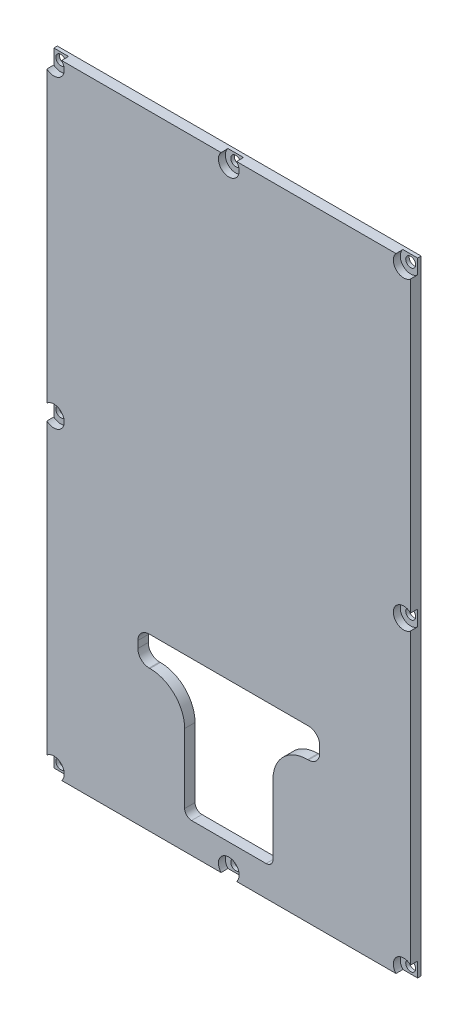
SolidWorks part; units mm, degrees
ref_plane "Спереди" through (0, 0, 0) normal (0, 0, 1) x (1, 0, 0)
ref_plane "Сверху" through (0, 0, 0) normal (0, 1, 0) x (1, 0, 0)
ref_plane "Справа" through (0, 0, 0) normal (1, 0, 0) x (0, 0, -1)
sketch "Эскиз1" plane through (0, 0, 0) normal (0, 0, 1) x (1, 0, 0)
  line L1 (-52.5, -90) -> (52.5, -90)
  line L2 (-52.5, -90) -> (-52.5, 90)
  line L3 (-52.5, 90) -> (52.5, 90)
  line L4 (52.5, -90) -> (52.5, 90)
  line L5 (-52.5, -90) -> (52.5, 90) construction
  line L6 (-52.5, 90) -> (52.5, -90) construction
  point P0 (0, 0)
  dimension "D1" = 105
  dimension "D2" = 180
extrude "Бобышка-Вытянуть1" add sketch "Эскиз1" along normal blind 3
sketch "Эскиз2" plane through (0, 0, 0) normal (0, 0, -1) x (-1, 0, 0)
  line L0 (-26.25, -44) -> (-26.25, -46)
  line L1 (-23, -49.25) -> (-22.75, -49.25)
  line L2 (-12.75, -59.25) -> (-12.75, -79.25)
  line L3 (-10.75, -81.25) -> (10.75, -81.25)
  line L4 (12.75, -79.25) -> (12.75, -59.25)
  line L5 (22.75, -49.25) -> (23, -49.25)
  line L6 (26.25, -46) -> (26.25, -44)
  line L7 (23, -40.75) -> (-23, -40.75)
  line L8 (-52.5, -90) -> (-52.5, 90) construction
  line L9 (52.5, 90) -> (52.5, -90) construction
  line L10 (52.5, -90) -> (-52.5, -90) construction
  arc A0 (22.75, -49.25) -> (12.75, -59.25) centre (22.75, -59.25) ccw
  arc A1 (-12.75, -59.25) -> (-22.75, -49.25) centre (-22.75, -59.25) ccw
  arc A2 (23, -49.25) -> (26.25, -46) centre (23, -46) ccw
  arc A3 (26.25, -44) -> (23, -40.75) centre (23, -44) ccw
  arc A4 (-23, -49.25) -> (-26.25, -46) centre (-23, -46) cw
  arc A5 (-23, -40.75) -> (-26.25, -44) centre (-23, -44) ccw
  arc A6 (12.75, -79.25) -> (10.75, -81.25) centre (10.75, -79.25) cw
  arc A7 (-10.75, -81.25) -> (-12.75, -79.25) centre (-10.75, -79.25) cw
  point P16 (12.75, -49.25)
  point P21 (26.25, -49.25)
  point P24 (26.25, -40.75)
  point P31 (12.75, -81.25)
  point P34 (-12.75, -81.25)
  dimension "D7" = 10
  dimension "D8" = 3.25
  dimension "D9" = 2
  dimension "D1" = 26.25
  dimension "D2" = 26.25
  dimension "D3" = 49.25
  dimension "D4" = 8.5
  dimension "D5" = 25.5
  dimension "D6" = 32
extrude "Вырез-Вытянуть1" cut sketch "Эскиз2" against normal blind 10
sketch "Эскиз3" plane through (0, 0, 3) normal (0, 0, 1) x (1, 0, 0)
  line L0 (-50.5, -940.9285) -> (-50.5, 49059.0715) construction
  line L1 (50.5, -944.6511) -> (50.5, 49055.3489) construction
  line L2 (-1032.3277, 88) -> (48967.6723, 88) construction
  line L3 (-1028.801, -88) -> (48971.199, -88) construction
  line L4 (-52.5, -90) -> (52.5, -90) construction
  line L6 (-52.5, 90) -> (-52.5, -90) construction
  line L7 (52.5, -90) -> (52.5, 90) construction
  line L8 (52.5, 90) -> (-52.5, 90) construction
  line L9 (0, -925) -> (0, 49075) construction
  line L10 (-1052.5, 0) -> (48947.5, 0) construction
  circle A0 centre (-50.5, 88) radius 3
  circle A1 centre (0, 88) radius 3
  circle A2 centre (50.5, 88) radius 3
  circle A3 centre (50.5, 0) radius 3
  circle A4 centre (50.5, -88) radius 3
  circle A5 centre (0, -88) radius 3
  circle A6 centre (-50.5, -88) radius 3
  circle A7 centre (-50.5, 0) radius 3
  point P19 (0, 90)
  point P22 (-52.5, 0)
  dimension "D5" = 6
  dimension "D1" = 2
  dimension "D2" = 2
  dimension "D3" = 2
  dimension "D4" = 2
extrude "Вырез-Вытянуть2" cut sketch "Эскиз3" against normal blind 2
sketch "Эскиз4" plane through (0, 0, 1) normal (0, 0, 1) x (1, 0, 0)
  circle A0 centre (-50.5, 88) radius 1.425
  circle A1 centre (0, 88) radius 1.425
  circle A2 centre (50.5, 88) radius 1.425
  circle A3 centre (50.5, 0) radius 1.425
  circle A4 centre (50.5, -88) radius 1.425
  circle A5 centre (0, -88) radius 1.425
  circle A6 centre (-50.5, -88) radius 1.425
  circle A7 centre (-50.5, 0) radius 1.425
  dimension "D1" = 2.85
extrude "Вырез-Вытянуть3" cut sketch "Эскиз4" against normal blind 2
